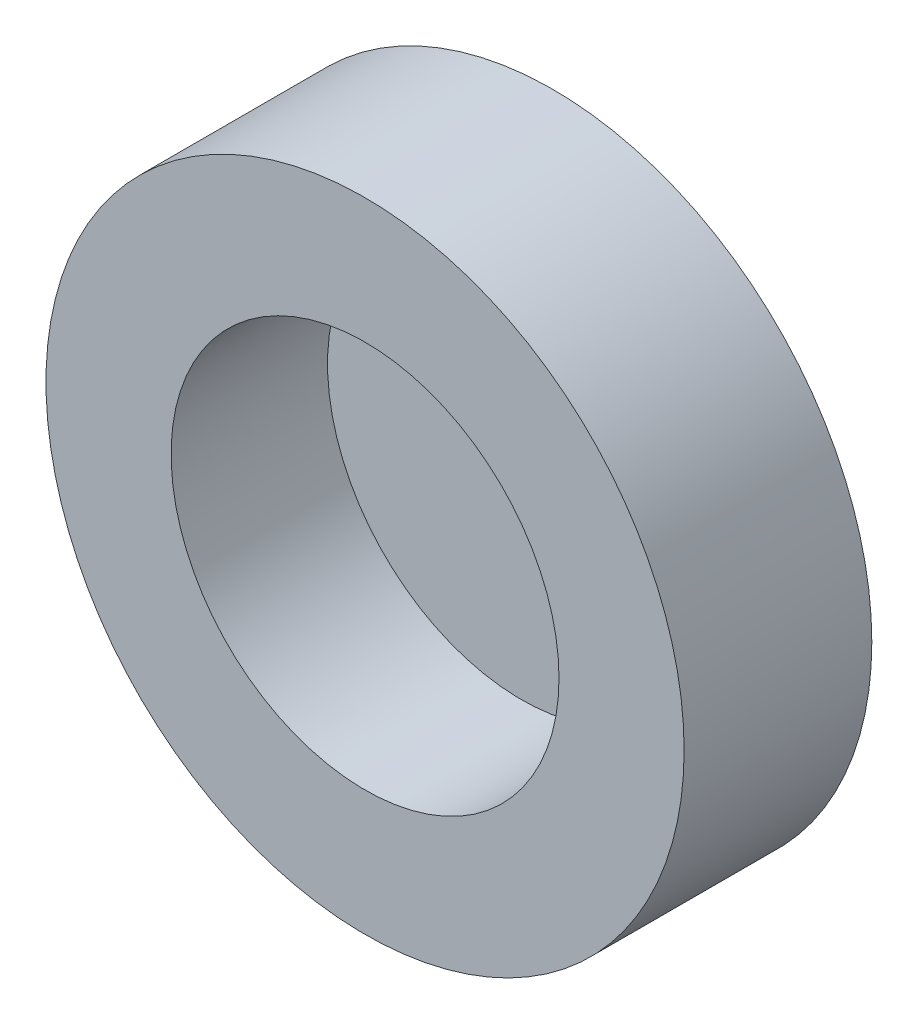
SolidWorks part; units mm, degrees
ref_plane "前视基准面" through (0, 0, 0) normal (0, 0, 1) x (1, 0, 0)
ref_plane "上视基准面" through (0, 0, 0) normal (0, 1, 0) x (1, 0, 0)
ref_plane "右视基准面" through (0, 0, 0) normal (1, 0, 0) x (0, 0, -1)
sketch "草图1" plane through (0, 0, 0) normal (0, 0, 1) x (1, 0, 0)
  circle A0 centre (0, 0) radius 1
  dimension "D1" = 2
extrude "凸台-拉伸1" add sketch "草图1" along normal blind 5.5
sketch "草图2" plane through (0, 0, 5.5) normal (0, 0, 1) x (1, 0, 0)
  circle A1 centre (0, 0) radius 5.1
  dimension "D1" = 10.2
extrude "凸台-拉伸2" add sketch "草图2" against normal blind 3
sketch "草图3" plane through (0, 0, 5.5) normal (0, 0, 1) x (1, 0, 0)
  circle A0 centre (0, 0) radius 3.1
  dimension "D1" = 6.2
extrude "切除-拉伸1" cut sketch "草图3" against normal blind 2.5
